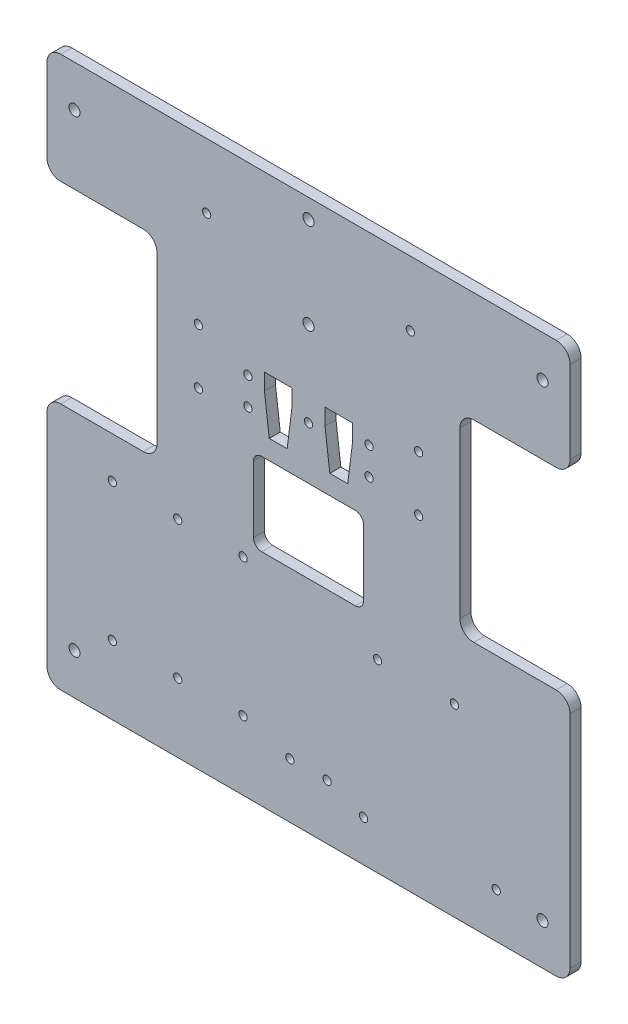
SolidWorks part; units mm, degrees
ref_plane "Front" through (0, 0, 0) normal (0, 0, 1) x (1, 0, 0)
ref_plane "Top" through (0, 0, 0) normal (0, 1, 0) x (1, 0, 0)
ref_plane "Right" through (0, 0, 0) normal (1, 0, 0) x (0, 0, -1)
sketch "Sketch1" plane through (0, 0, 0) normal (0, 0, 1) x (1, 0, 0)
  line L0 (-95, -115) -> (-95, -195)
  line L1 (-90, 0) -> (90, 0)
  line L2 (-95, -5) -> (-95, -35)
  line L3 (-90, -200) -> (90, -200)
  line L4 (95, -5) -> (95, -35)
  line L5 (-90, -40) -> (-60, -40)
  line L7 (-90, -110) -> (-60, -110)
  line L8 (-55, -45) -> (-55, -105)
  line L9 (90, -40) -> (60, -40)
  line L11 (90, -110) -> (60, -110)
  line L12 (55, -45) -> (55, -105)
  line L13 (95, -115) -> (95, -195)
  arc A0 (-95, -195) -> (-90, -200) centre (-90, -195) ccw
  arc A1 (95, -5) -> (90, 0) centre (90, -5) ccw
  arc A2 (-90, 0) -> (-95, -5) centre (-90, -5) ccw
  arc A3 (90, -200) -> (95, -195) centre (90, -195) ccw
  arc A4 (95, -35) -> (90, -40) centre (90, -35) cw
  arc A5 (95, -115) -> (90, -110) centre (90, -115) ccw
  arc A6 (60, -40) -> (55, -45) centre (60, -45) ccw
  arc A7 (60, -110) -> (55, -105) centre (60, -105) cw
  arc A8 (-95, -115) -> (-90, -110) centre (-90, -115) cw
  arc A9 (-60, -110) -> (-55, -105) centre (-60, -105) ccw
  arc A10 (-60, -40) -> (-55, -45) centre (-60, -45) cw
  arc A11 (-90, -40) -> (-95, -35) centre (-90, -35) cw
  point P4 (0, 0)
  point P10 (95, 0)
  point P13 (-95, 0)
  point P16 (95, -200)
  point P27 (95, -40)
  point P32 (55, -40)
  point P35 (55, -110)
  point P40 (-55, -110)
  point P43 (-55, -40)
  point P46 (-95, -40)
  dimension "D3" = 5
  dimension "D4" = 5
  dimension "D5" = 5
  dimension "D6" = 5
  dimension "D12" = 5
  dimension "D1" = 190
  dimension "D2" = 200
  dimension "D7" = 40
  dimension "D8" = 40
  dimension "D9" = 40
  dimension "D10" = 70
  dimension "D11" = 70
  dimension "D13" = 40
extrude "Boss-Extrude1" add sketch "Sketch1" along normal blind 4
sketch "Sketch2" plane through (0, 0, 4) normal (0, 0, 1) x (1, 0, 0)
  line L0 (0, -218.7659) -> (0, 71.8391) construction
  line L1 (-95, -5) -> (-95, -35) construction
  line L2 (-90, -200) -> (90, -200) construction
  line L3 (90, 0) -> (-90, 0) construction
  line L4 (-90, -200) -> (90, -200) construction
  circle A0 centre (-85, -185) radius 2
  circle A1 centre (-85, -15) radius 2
  circle A2 centre (85, -15) radius 2
  circle A3 centre (85, -185) radius 2
  circle A4 centre (-6.765, -180) radius 1.5
  circle A5 centre (6.765, -180) radius 1.5
  dimension "D1" = 4
  dimension "D2" = 4
  dimension "D7" = 13.53
  dimension "D3" = 10
  dimension "D4" = 15
  dimension "D5" = 15
  dimension "D6" = 10
  dimension "D8" = 20
extrude "Cut-Extrude1" cut sketch "Sketch2" against normal blind 20
sketch "Sketch3" plane through (0, 0, 4) normal (0, 0, 1) x (1, 0, 0)
  line L0 (0, 38.5018) -> (0, -275.6294) construction
  line L1 (-47.5, 21.4724) -> (-47.5, -234.3108) construction
  line L2 (-148.4478, -100) -> (135.558, -100) construction
  line L3 (-122.1233, -50) -> (119.5593, -50) construction
  line L4 (90, 0) -> (-90, 0) construction
  line L5 (-95, -5) -> (-95, -35) construction
  circle A1 centre (-71.25, -75) radius 1.5
  circle A2 centre (-71.25, -175) radius 1.5
  circle A3 centre (-71.25, -125) radius 1.5
  circle A14 centre (71.25, -75) radius 1.5
  circle A16 centre (-23.75, -125) radius 1.5
  circle A17 centre (-23.75, -175) radius 1.5
  circle A18 centre (-47.5, -125) radius 1.5
  circle A19 centre (-47.5, -175) radius 1.5
  dimension "D8" = 3
  dimension "D9" = 3
  dimension "D1" = 50
  dimension "D2" = 100
  dimension "D3" = 47.5
  dimension "D4" = 95
extrude "Cut-Extrude2" cut sketch "Sketch3" against normal blind 10
sketch "Sketch4" plane through (0, 0, 4) normal (0, 0, 1) x (1, 0, 0)
  line L0 (-6.765, -180) -> (6.765, -180) construction
sketch "Sketch5" plane through (0, 0, 4) normal (0, 0, 1) x (1, 0, 0)
  line L0 (0, 0) -> (0, -200) construction
  line L3 (-90, -200) -> (90, -200) construction
  line L4 (-55, -45) -> (-55, -105) construction
  line L5 (-90, -40) -> (-60, -40) construction
  line L6 (-90, -200) -> (90, -200) construction
  line L7 (90, 0) -> (-90, 0) construction
  line L8 (-37, -23.5) -> (37, -23.5) construction
  line L9 (0, -7) -> (0, -40) construction
  circle A4 centre (-40, -60) radius 1.5
  circle A5 centre (-40, -80) radius 1.5
  circle A6 centre (40, -80) radius 1.5
  circle A7 centre (40, -60) radius 1.5
  circle A9 centre (25.1, -132.9) radius 1.5
  circle A10 centre (20, -185) radius 1.5
  circle A11 centre (68.2, -183.7) radius 1.5
  circle A13 centre (53, -132.9) radius 1.5
  circle A14 centre (0, -7) radius 2
  circle A15 centre (0, -40) radius 2
  circle A16 centre (-37, -23.5) radius 1.5
  circle A17 centre (37, -23.5) radius 1.5
  point P42 (0, -23.5)
  point P44 (0, -23.5)
  dimension "D2" = 3
  dimension "D3" = 3
  dimension "D4" = 3
  dimension "D5" = 3
  dimension "D9" = 50.8
  dimension "D11" = 3
  dimension "D13" = 3
  dimension "D16" = 20
  dimension "D17" = 20
  dimension "D7" = 15.2
  dimension "D8" = 5.1
  dimension "D10" = 52.1
  dimension "D19" = 4
  dimension "D20" = 4
  dimension "D21" = 33
  dimension "D22" = 7
  dimension "D23" = 37
  dimension "D24" = 3
  dimension "D25" = 3
  dimension "D6" = 27.9
  dimension "D12" = 15
  dimension "D14" = 15
  dimension "D15" = 15
  dimension "D18" = 20
extrude "Cut-Extrude3" cut sketch "Sketch5" against normal through all
sketch "Sketch7" plane through (0, 0, 0) normal (0, 0, -1) x (-1, 0, 0)
  line L0 (0, 20.9768) -> (0, -223.1934) construction
  line L1 (-90, 0) -> (90, 0) construction
  line L2 (17, -120) -> (-17, -120)
  line L3 (20, -117) -> (20, -93)
  line L4 (17, -90) -> (-17, -90)
  line L5 (-20, -117) -> (-20, -93)
  line L7 (16, -62.9774) -> (6, -62.9774)
  line L9 (14.25, -82.9774) -> (7.75, -82.9774)
  line L14 (16, -62.9774) -> (16, -68.9774)
  line L15 (16, -68.9774) -> (14.25, -82.9774)
  line L16 (6, -62.9774) -> (6, -68.9774)
  line L17 (6, -68.9774) -> (7.75, -82.9774)
  line L18 (-6, -68.9774) -> (-7.75, -82.9774)
  line L19 (-6, -62.9774) -> (-6, -68.9774)
  line L20 (-16, -68.9774) -> (-14.25, -82.9774)
  line L21 (-16, -62.9774) -> (-16, -68.9774)
  line L22 (-14.25, -82.9774) -> (-7.75, -82.9774)
  line L23 (-16, -62.9774) -> (-6, -62.9774)
  arc A4 (-17, -120) -> (-20, -117) centre (-17, -117) cw
  arc A5 (-17, -90) -> (-20, -93) centre (-17, -93) ccw
  arc A6 (20, -93) -> (17, -90) centre (17, -93) ccw
  arc A7 (17, -120) -> (20, -117) centre (17, -117) ccw
  circle A8 centre (22, -66.9774) radius 1.5
  circle A9 centre (22.0092, -76.9774) radius 1.5
  circle A16 centre (-22.0092, -76.9774) radius 1.5
  circle A17 centre (-22, -66.9774) radius 1.5
  circle A18 centre (0, -70.9774) radius 1.5
  point P15 (0, -120)
  point P20 (-20, -120)
  point P23 (-20, -90)
  point P28 (20, -120)
  point P34 (11, -62.9774)
  point P37 (11, -82.9774)
  dimension "D2" = 3
  dimension "D8" = 3
  dimension "D9" = 10
  dimension "D3" = 3
  dimension "D4" = 10
  dimension "D12" = 4
  dimension "D13" = 6
  dimension "D14" = 6
  dimension "D15" = 6
  dimension "D11" = 6
  dimension "D17" = 3
  dimension "D5" = 40
  dimension "D6" = 30
  dimension "D7" = 120
  dimension "D10" = 6.5
  dimension "D16" = 6
extrude "Cut-Extrude4" cut sketch "Sketch7" against normal blind 10
